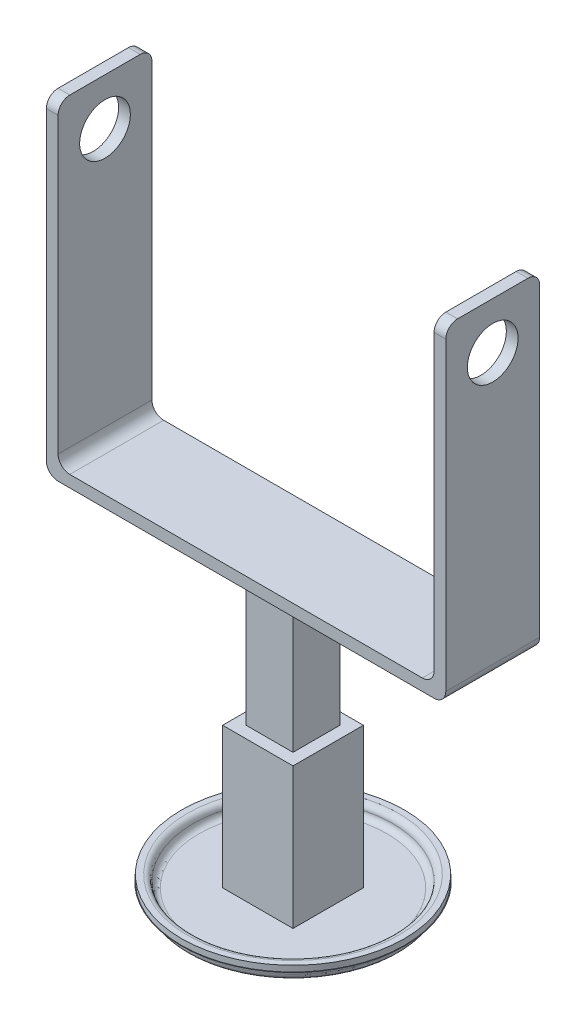
SolidWorks part; units mm, degrees
other "DetailItem7"
ref_plane "Front Plane" through (0, 0, 0) normal (0, 0, 1) x (1, 0, 0)
ref_plane "Top Plane" through (0, 0, 0) normal (0, 1, 0) x (1, 0, 0)
ref_plane "Right Plane" through (0, 0, 0) normal (1, 0, 0) x (0, 0, -1)
sketch "Sketch2" plane through (0, 0, 0) normal (0, 0, 1) x (1, 0, 0)
  line L0 (0, 0) -> (54.2617, 0)
  line L2 (60.6117, 6.35) -> (60.325, 6.35)
  line L3 (60.325, 6.35) -> (60.325, 9.525)
  line L4 (60.325, 9.525) -> (57.15, 9.525)
  line L6 (50.8, 3.175) -> (0, 3.175)
  line L7 (0, 3.175) -> (0, 0)
  arc A0 (53.975, 6.35) -> (50.8, 3.175) centre (50.8, 6.35) cw
  arc A1 (57.15, 9.525) -> (53.975, 6.35) centre (57.15, 6.35) ccw
  arc A2 (57.4367, 3.175) -> (60.6117, 6.35) centre (60.6117, 3.175) cw
  arc A3 (54.2617, 0) -> (57.4367, 3.175) centre (54.2617, 3.175) ccw
  point P16 (53.975, 3.175)
  dimension "D3" = 3.175
  dimension "D1" = 50.8
  dimension "D2" = 3.175
  dimension "D4" = 60.325
  dimension "D5" = 3.175
revolve "Revolve1" add sketch "Sketch2" angle 360 about L7
sketch "Sketch3" plane through (0, 3.175, 0) normal (0, 1, 0) x (1, 0, 0)
  line L1 (19.05, 19.05) -> (-19.05, 19.05)
  line L2 (19.05, 19.05) -> (19.05, -19.05)
  line L3 (19.05, -19.05) -> (-19.05, -19.05)
  line L4 (-19.05, 19.05) -> (-19.05, -19.05)
  line L5 (19.05, 19.05) -> (-19.05, -19.05) construction
  line L6 (19.05, -19.05) -> (-19.05, 19.05) construction
  point P0 (0, 0)
  dimension "D1" = 38.1
  dimension "D2" = 38.1
extrude "Boss-Extrude1" add sketch "Sketch3" along normal blind 76.2
sketch "Sketch4" plane through (0, 79.375, 0) normal (0, 1, 0) x (1, 0, 0)
  line L1 (12.7, 12.7) -> (-12.7, 12.7)
  line L2 (12.7, 12.7) -> (12.7, -12.7)
  line L3 (12.7, -12.7) -> (-12.7, -12.7)
  line L4 (-12.7, 12.7) -> (-12.7, -12.7)
  line L5 (12.7, 12.7) -> (-12.7, -12.7) construction
  line L6 (12.7, -12.7) -> (-12.7, 12.7) construction
  point P0 (0, 0)
  dimension "D1" = 25.4
  dimension "D2" = 25.4
extrude "Boss-Extrude2" add sketch "Sketch4" along normal blind 76.2
sketch "Sketch5" plane through (0, 0, 0) normal (0, 0, 1) x (1, 0, 0)
  line L0 (108.077, 155.575) -> (-108.077, 155.575)
  line L1 (12.7, 155.575) -> (-12.7, 155.575) construction
  line L3 (108.077, 155.575) -> (108.077, 333.375)
  line L4 (-108.077, 155.575) -> (-108.077, 333.375)
  line L5 (-108.077, 333.375) -> (-101.727, 333.375)
  line L6 (-101.727, 333.375) -> (-101.727, 161.925)
  line L7 (-101.727, 161.925) -> (101.727, 161.925)
  line L8 (101.727, 161.925) -> (101.727, 333.375)
  line L9 (101.727, 333.375) -> (108.077, 333.375)
  point P3 (-4.8132, 179.0091)
  point P4 (0, 155.575)
  point P6 (-104.902, 333.375)
  point P11 (0, 0)
  point P12 (0, 155.575)
  point P13 (0, 0)
  point P15 (0, 0)
  point P17 (0, 155.575)
  dimension "D1" = 203.454
  dimension "D2" = 6.35
  dimension "D3" = 6.35
  dimension "D4" = 6.35
  dimension "D5" = 177.8
extrude "Boss-Extrude3" add sketch "Sketch5" along normal mid plane 50.8
fillet "Fillet1" radius 6.35 1 edges at (101.727, 161.925, 0)
fillet "Fillet2" radius 6.35 1 edges at (-101.727, 161.925, 0)
fillet "Fillet3" radius 6.35 2 edges at (-108.077, 155.575, 0) (108.077, 155.575, 0)
fillet "Fillet4" radius 6.35 4 edges at (-104.902, 333.375, -25.4) (-104.902, 333.375, 25.4) (104.902, 333.375, 25.4) (104.902, 333.375, -25.4)
sketch "Sketch6" plane through (108.077, 0, 0) normal (1, 0, 0) x (0, 0, -1)
  line L0 (0, 333.375) -> (0, 161.925) construction
  line L1 (-19.05, 333.375) -> (19.05, 333.375) construction
  line L2 (-25.4, 161.925) -> (25.4, 161.925) construction
  line L3 (-87.8855, 307.975) -> (163.148, 307.975) construction
  circle A0 centre (0, 307.975) radius 13.716
  dimension "D2" = 27.432
  dimension "D1" = 25.4
extrude "Cut-Extrude1" cut sketch "Sketch6" against normal through all
